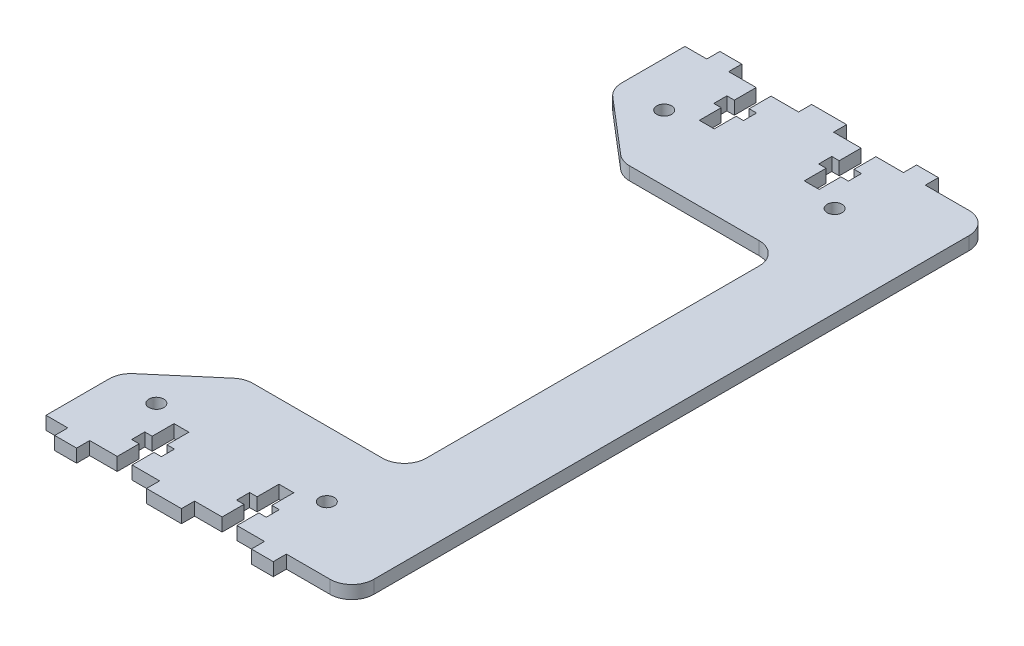
SolidWorks part; units mm, degrees
material "Thornel Mat VMA"
ref_plane "前视基准面" through (0, 0, 0) normal (0, 0, 1) x (1, 0, 0)
ref_plane "上视基准面" through (0, 0, 0) normal (0, 1, 0) x (1, 0, 0)
ref_plane "右视基准面" through (0, 0, 0) normal (1, 0, 0) x (0, 0, -1)
sketch "草图1" plane through (0, 0, 0) normal (0, 1, 0) x (1, 0, 0)
  line L0 (-25, -73.1) -> (-25, -76.1)
  line L1 (-35, -73.1) -> (-25, -73.1)
  line L2 (-35, -73.1) -> (-35, 73.1)
  line L3 (-35, 73.1) -> (-25, 73.1)
  line L4 (35, -73.1) -> (35, 73.1)
  line L5 (-35, -73.1) -> (35, 73.1) construction
  line L6 (-35, 73.1) -> (35, -73.1) construction
  line L7 (-25, -76.1) -> (-20, -76.1)
  line L8 (-20, -76.1) -> (-20, -73.1)
  line L9 (-4, -73.1) -> (-4, -76.1)
  line L10 (-4, -76.1) -> (4, -76.1)
  line L11 (4, -76.1) -> (4, -73.1)
  line L12 (20, -73.1) -> (20, -76.1)
  line L13 (20, -76.1) -> (25, -76.1)
  line L14 (25, -76.1) -> (25, -73.1)
  line L15 (-13.7, -73.1) -> (-13.7, -68.1)
  line L16 (-13.7, -68.1) -> (-15.4, -68.1)
  line L17 (-15.4, -68.1) -> (-15.4, -65.1)
  line L18 (-15.4, -65.1) -> (-13.7, -65.1)
  line L19 (-13.7, -65.1) -> (-13.7, -60.1)
  line L20 (-13.7, -60.1) -> (-10.3, -60.1)
  line L21 (-10.3, -60.1) -> (-10.3, -65.1)
  line L22 (-10.3, -65.1) -> (-8.6, -65.1)
  line L23 (-8.6, -65.1) -> (-8.6, -68.1)
  line L24 (-8.6, -68.1) -> (-10.3, -68.1)
  line L25 (-10.3, -68.1) -> (-10.3, -73.1)
  line L26 (10.3, -73.1) -> (10.3, -68.1)
  line L27 (10.3, -68.1) -> (8.6, -68.1)
  line L28 (8.6, -68.1) -> (8.6, -65.1)
  line L29 (8.6, -65.1) -> (10.3, -65.1)
  line L30 (10.3, -65.1) -> (10.3, -60.1)
  line L31 (10.3, -60.1) -> (13.7, -60.1)
  line L32 (13.7, -60.1) -> (13.7, -65.1)
  line L33 (13.7, -65.1) -> (15.4, -65.1)
  line L34 (15.4, -65.1) -> (15.4, -68.1)
  line L35 (15.4, -68.1) -> (13.7, -68.1)
  line L36 (13.7, -68.1) -> (13.7, -73.1)
  line L37 (0, 0) -> (35, 0) construction
  line L38 (-25, 73.1) -> (-25, 76.1)
  line L39 (-25, 76.1) -> (-20, 76.1)
  line L40 (-20, 76.1) -> (-20, 73.1)
  line L41 (-4, 73.1) -> (-4, 76.1)
  line L42 (-4, 76.1) -> (4, 76.1)
  line L43 (4, 76.1) -> (4, 73.1)
  line L44 (20, 73.1) -> (20, 76.1)
  line L45 (25, 76.1) -> (25, 73.1)
  line L46 (20, 76.1) -> (25, 76.1)
  line L47 (10.3, 68.1) -> (8.6, 68.1)
  line L48 (10.3, 73.1) -> (10.3, 68.1)
  line L49 (13.7, 68.1) -> (13.7, 73.1)
  line L50 (15.4, 68.1) -> (13.7, 68.1)
  line L51 (15.4, 65.1) -> (15.4, 68.1)
  line L52 (13.7, 65.1) -> (15.4, 65.1)
  line L53 (8.6, 68.1) -> (8.6, 65.1)
  line L54 (8.6, 65.1) -> (10.3, 65.1)
  line L55 (10.3, 65.1) -> (10.3, 60.1)
  line L56 (13.7, 60.1) -> (13.7, 65.1)
  line L57 (10.3, 60.1) -> (13.7, 60.1)
  line L58 (-15.4, 65.1) -> (-13.7, 65.1)
  line L59 (-15.4, 68.1) -> (-15.4, 65.1)
  line L60 (-13.7, 68.1) -> (-15.4, 68.1)
  line L61 (-13.7, 73.1) -> (-13.7, 68.1)
  line L63 (-10.3, 68.1) -> (-10.3, 73.1)
  line L64 (-8.6, 68.1) -> (-10.3, 68.1)
  line L65 (-8.6, 65.1) -> (-8.6, 68.1)
  line L66 (-10.3, 65.1) -> (-8.6, 65.1)
  line L67 (-13.7, 65.1) -> (-13.7, 60.1)
  line L68 (-10.3, 60.1) -> (-10.3, 65.1)
  line L69 (-13.7, 60.1) -> (-10.3, 60.1)
  line L70 (-20, 73.1) -> (-13.7, 73.1)
  line L71 (-10.3, 73.1) -> (-4, 73.1)
  line L72 (4, 73.1) -> (10.3, 73.1)
  line L73 (13.7, 73.1) -> (20, 73.1)
  line L74 (25, 73.1) -> (35, 73.1)
  line L75 (-20, -73.1) -> (-13.7, -73.1)
  line L77 (-10.3, -73.1) -> (-4, -73.1)
  line L79 (4, -73.1) -> (10.3, -73.1)
  line L81 (13.7, -73.1) -> (20, -73.1)
  line L83 (25, -73.1) -> (35, -73.1)
  point P0 (0, 0)
  point P32 (-12, -60.1)
  point P43 (12, -60.1)
  dimension "D1" = 70
  dimension "D2" = 146.2
  dimension "D3" = 5
  dimension "D4" = 3
  dimension "D5" = 3
  dimension "D6" = 8
  dimension "D7" = 3
  dimension "D8" = 5
  dimension "D9" = 3.4
  dimension "D10" = 3.4
  dimension "D11" = 1.7
  dimension "D12" = 1.7
  dimension "D13" = 1.7
  dimension "D14" = 1.7
  dimension "D15" = 3
  dimension "D16" = 3
  dimension "D17" = 5
  dimension "D18" = 5
  dimension "D19" = 5
  dimension "D20" = 1.7
  dimension "D21" = 1.7
  dimension "D22" = 1.7
  dimension "D23" = 1.7
  dimension "D24" = 5
  dimension "D25" = 5
  dimension "D26" = 3
  dimension "D27" = 3
  dimension "D28" = 5
  dimension "D29" = 5
  dimension "D30" = 8
  dimension "D31" = 8
  dimension "D32" = 16
  dimension "D34" = 16
extrude "凸台-拉伸1" add sketch "草图1" along normal blind 3
sketch "草图2" plane through (0, 0, 73.1) normal (0, 0, 1) x (1, 0, 0)
  line L0 (-35, 0) -> (-25, 0) construction
  line L1 (-35, 3) -> (-30, 3)
  line L2 (-35, 3) -> (-35, 0)
  line L3 (-35, 0) -> (-30, 0)
  line L4 (-30, 3) -> (-30, 0)
  line L5 (-35, 3) -> (-30, 0) construction
  line L6 (-35, 0) -> (-30, 3) construction
  point P4 (-32.5, 1.5)
  point P12 (32.5, 1.5)
  dimension "D2" = 5
extrude "切除-拉伸1" cut sketch "草图2" against normal blind 176
sketch "草图3" plane through (35, 0, 0) normal (1, 0, 0) x (0, 0, -1)
  line L4 (-73.1, 0) -> (73.1, 0)
  line L5 (73.1, 0) -> (73.1, 3)
  line L6 (73.1, 3) -> (-73.1, 3)
  line L7 (-73.1, 3) -> (-73.1, 0)
  line L8 (-73.1, 0) -> (73.1, 0)
  line L9 (73.1, 0) -> (73.1, 3)
  line L10 (73.1, 3) -> (-73.1, 3)
  line L11 (-73.1, 3) -> (-73.1, 0)
  dimension "D1" = 0
extrude "凸台-拉伸2" add sketch "草图3" along normal blind 5
sketch "草图4" plane through (0, 3, 0) normal (0, 1, 0) x (1, 0, 0)
  line L0 (-25, 73.1) -> (-30, 73.1) construction
  line L1 (-30, 73.1) -> (-30, -73.1) construction
  line L2 (40, 73.1) -> (25, 73.1) construction
  line L3 (40, 73.1) -> (40, -73.1) construction
  line L4 (-30, -73.1) -> (-25, -73.1) construction
  line L5 (25, -73.1) -> (40, -73.1) construction
  circle A0 centre (-19.75, -58.1) radius 1.7
  circle A1 centre (19.25, -58.1) radius 1.7
  circle A2 centre (19.25, 58.1) radius 1.7
  circle A3 centre (-19.75, 58.1) radius 1.7
  dimension "D1" = 3.4
  dimension "D2" = 3.4
  dimension "D3" = 3.4
  dimension "D4" = 3.4
  dimension "D5" = 15
  dimension "D6" = 10.25
  dimension "D7" = 15
  dimension "D8" = 20.75
  dimension "D9" = 15
  dimension "D10" = 10.25
  dimension "D11" = 15
  dimension "D12" = 20.75
extrude "切除-拉伸2" cut sketch "草图4" against normal blind 5
sketch "草图5" plane through (0, 3, 0) normal (0, 1, 0) x (1, 0, 0)
  line L0 (-30, -56.3314) -> (-14.5, -43.1)
  line L1 (-30, 73.1) -> (-30, -73.1) construction
  line L2 (-14.5, -43.1) -> (0, -43.1)
  line L3 (-30, 56.3314) -> (-14.5, 43.1)
  line L4 (-14.5, 43.1) -> (22, 43.1)
  line L5 (22, 43.1) -> (22, -43.1)
  line L6 (22, -43.1) -> (0, -43.1)
  line L7 (10.3, 73.1) -> (4, 73.1) construction
  line L8 (4, -73.1) -> (10.3, -73.1) construction
  line L9 (40, 73.1) -> (40, -73.1) construction
  line L10 (-30, 56.3314) -> (-30, -56.3314)
  circle A0 centre (-19.75, -58.1) radius 1.7 construction
  circle A1 centre (-19.75, 58.1) radius 1.7 construction
  dimension "D1" = 30
  dimension "D2" = 30
  dimension "D3" = 8
  dimension "D4" = 15.5
  dimension "D5" = 8
  dimension "D6" = 15.5
  dimension "D7" = 18
extrude "切除-拉伸3" cut sketch "草图5" against normal blind 10
fillet "圆角1" radius 5 6 edges at (-30, 1.5, 56.3314) (-14.5, 1.5, 43.1) (22, 1.5, 43.1) (22, 1.5, -43.1) (-14.5, 1.5, -43.1) (-30, 1.5, -56.3314)
fillet "圆角2" radius 5 2 edges at (40, 1.5, 73.1) (40, 1.5, -73.1)
